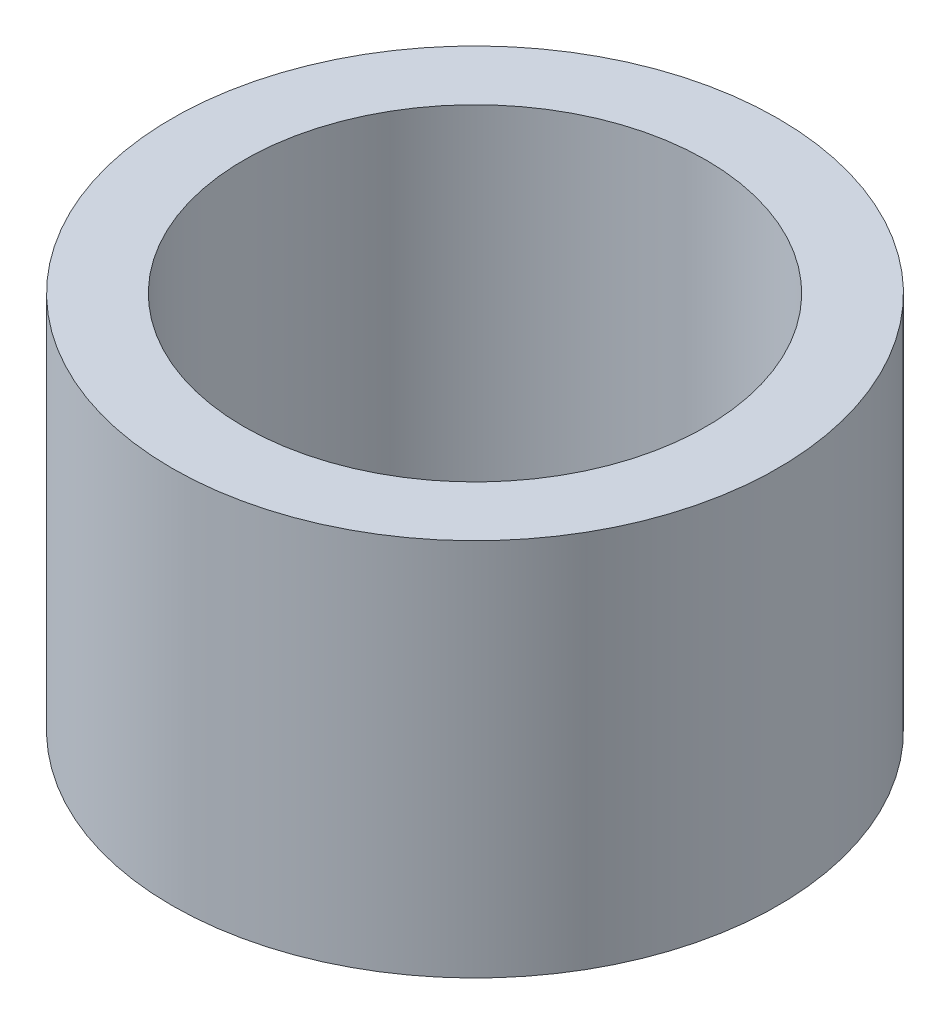
SolidWorks part; units mm, degrees
ref_plane "Front Plane" through (0, 0, 0) normal (0, 0, 1) x (1, 0, 0)
ref_plane "Top Plane" through (0, 0, 0) normal (0, 1, 0) x (1, 0, 0)
ref_plane "Right Plane" through (0, 0, 0) normal (1, 0, 0) x (0, 0, -1)
sketch "Sketch1" plane through (0, 0, 0) normal (0, 1, 0) x (1, 0, 0)
  circle A0 centre (0, 0) radius 3.05
  circle A1 centre (0, 0) radius 4
  dimension "D1" = 6.1
  dimension "D2" = 8
extrude "Boss-Extrude1" add sketch "Sketch1" along normal blind 5
